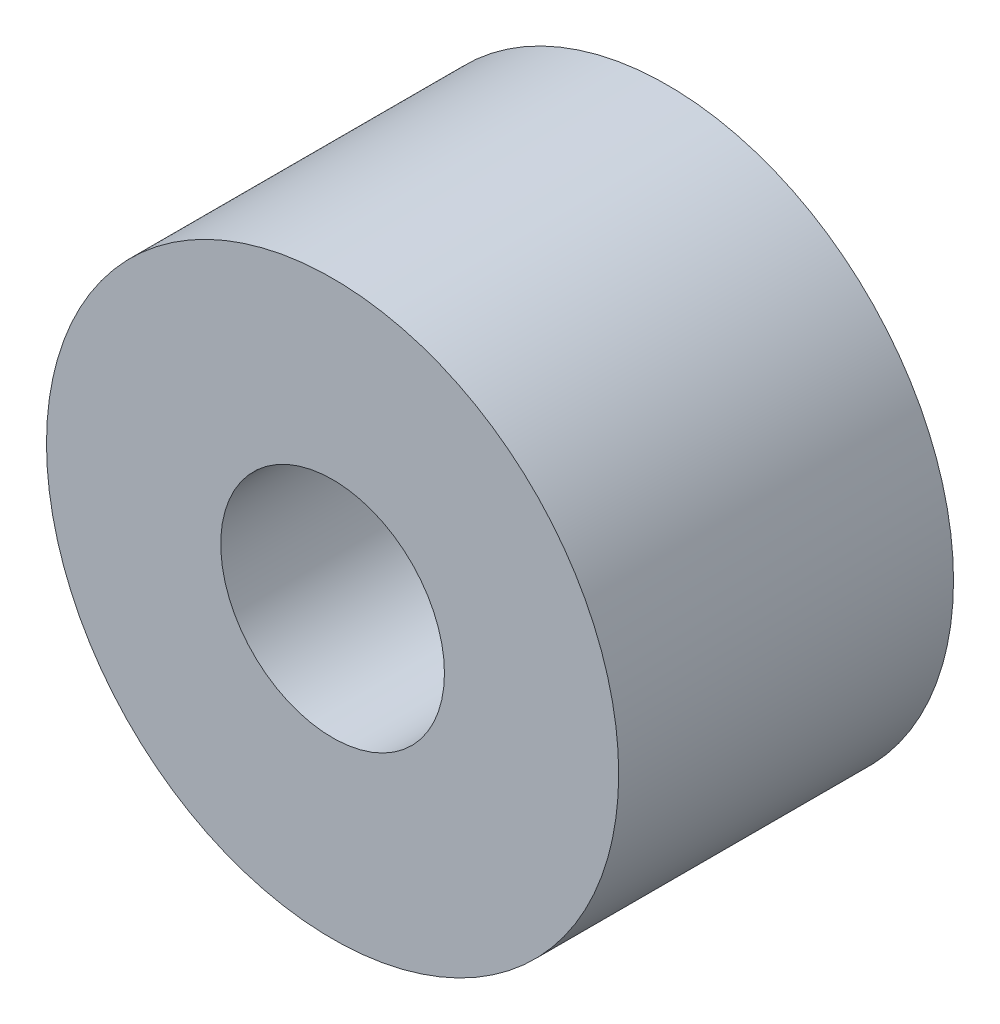
SolidWorks part; units mm, degrees
ref_plane "Front Plane" through (0, 0, 0) normal (0, 0, 1) x (1, 0, 0)
ref_plane "Top Plane" through (0, 0, 0) normal (0, 1, 0) x (1, 0, 0)
ref_plane "Right Plane" through (0, 0, 0) normal (1, 0, 0) x (0, 0, -1)
sketch "Sketch1" plane through (0, 0, 0) normal (0, 0, 1) x (1, 0, 0)
  circle A0 centre (0, 0) radius 4.775
  circle A1 centre (0, 0) radius 1.8669
  dimension "D1" = 9.55
  dimension "D2" = 3.7338
extrude "Boss-Extrude1" add sketch "Sketch1" along normal blind 5.588
